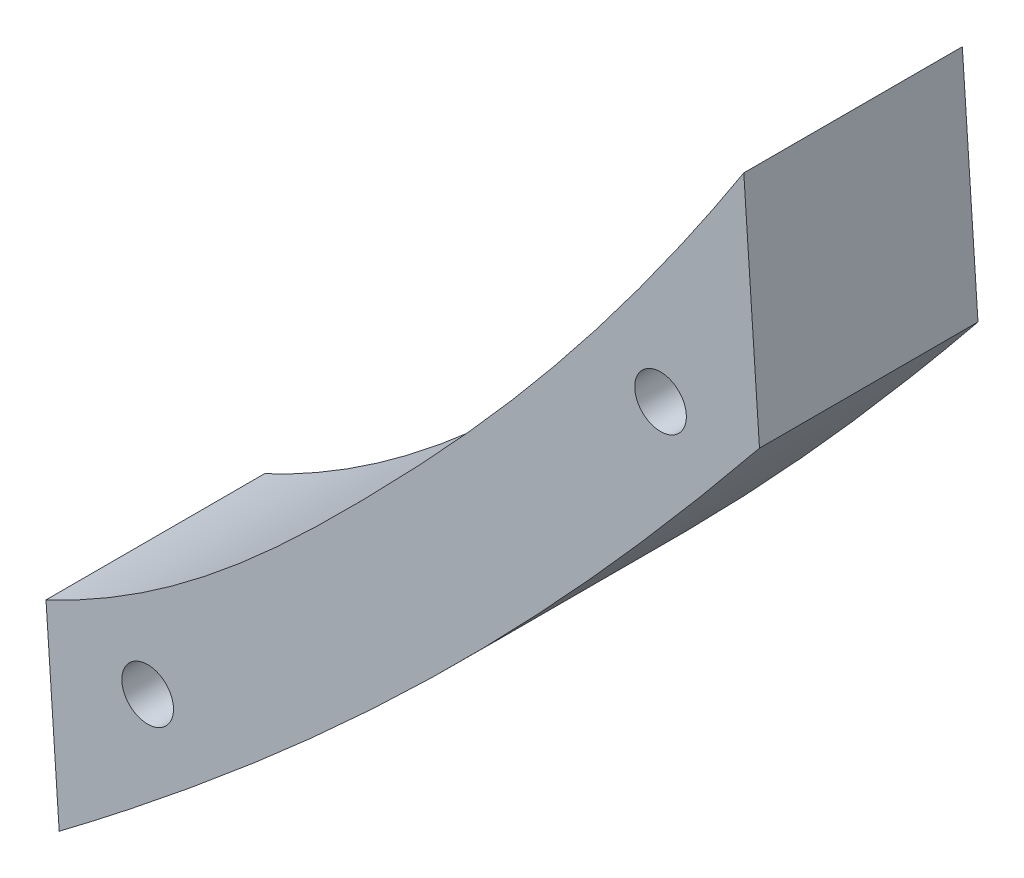
SolidWorks part; units mm, degrees
ref_plane "前视基准面" through (0, 0, 0) normal (0, 0, 1) x (1, 0, 0)
ref_plane "上视基准面" through (0, 0, 0) normal (0, 1, 0) x (1, 0, 0)
ref_plane "右视基准面" through (0, 0, 0) normal (1, 0, 0) x (0, 0, -1)
other "Configuration Table"
sketch "草图1" plane through (0, 0, 0) normal (0, 0, 1) x (1, 0, 0)
  line L0 (-46.4032, -49.8125) -> (-45.0756, -69.3257)
  line L1 (23.8473, 22.5405) -> (25.4266, -0.6704)
  circle A4 centre (-36.1679, -52.9315) radius 2.6
  circle A5 centre (15.4666, -1.5981) radius 2.6
  ellipse E0 centre (67.9619, 57.6316) end of major axis (68.6937, 56.9191) minor radius 0.6322 (68.7297, 56.9617) -> (68.7493, 56.9914) ccw
  spline S1 degree 3 poles (-45.0756, -69.3257) (-42.7543, -67.5744) (-40.4517, -65.7985) (-32.2943, -59.3685) (-26.5461, -54.5783) (-15.3451, -44.664) (-9.8956, -39.5366) (0.6813, -28.9591) (5.8082, -23.5096) (15.7635, -12.3444) (20.5923, -6.6307) (25.3447, -0.7714) (25.3857, -0.7209) (25.4266, -0.6704) knots 0.201402 0.201402 0.201402 0.201402 0.25 0.25 0.375 0.375 0.5 0.5 0.625 0.625 0.75 0.75 0.751087 0.751087 0.751087 0.751087
  spline S8 degree 3 poles (23.8473, 22.5405) (23.6492, 22.2333) (23.4505, 21.9264) (19.3022, 15.5396) (15.1597, 9.5852) (8.5968, 0.9153) (6.3513, -1.9312) (1.7446, -7.5283) (-0.6172, -10.2791) (-5.4459, -15.6859) (-7.9132, -18.3425) (-11.675, -22.268) (-12.939, -23.5671) (-15.4831, -26.1491) (-16.7624, -27.4328) (-20.64, -31.2437) (-23.2786, -33.7322) (-28.7493, -38.4912) (-31.5819, -40.7615) (-37.5022, -44.9481) (-40.5908, -46.863) (-44.6646, -48.9773) (-45.5296, -49.404) (-46.4032, -49.8125) knots 0.243696 0.243696 0.243696 0.243696 0.25 0.25 0.375 0.375 0.4375 0.4375 0.5 0.5 0.5625 0.5625 0.59375 0.59375 0.625 0.625 0.6875 0.6875 0.75 0.75 0.8125 0.8125 0.829123 0.829123 0.829123 0.829123
  point P16 (-45.7394, -59.5691)
  dimension "D7" = 5.2
  dimension "D8" = 5.2
  dimension "D2" = 75
  dimension "D9" = 10
  dimension "D10" = 10.7
  dimension "D11" = 10
  dimension "D12" = 9.96
extrude "凸台-拉伸1" add sketch "草图1" along normal blind 22 contours L1 S8 L0 S1 A4 A5
